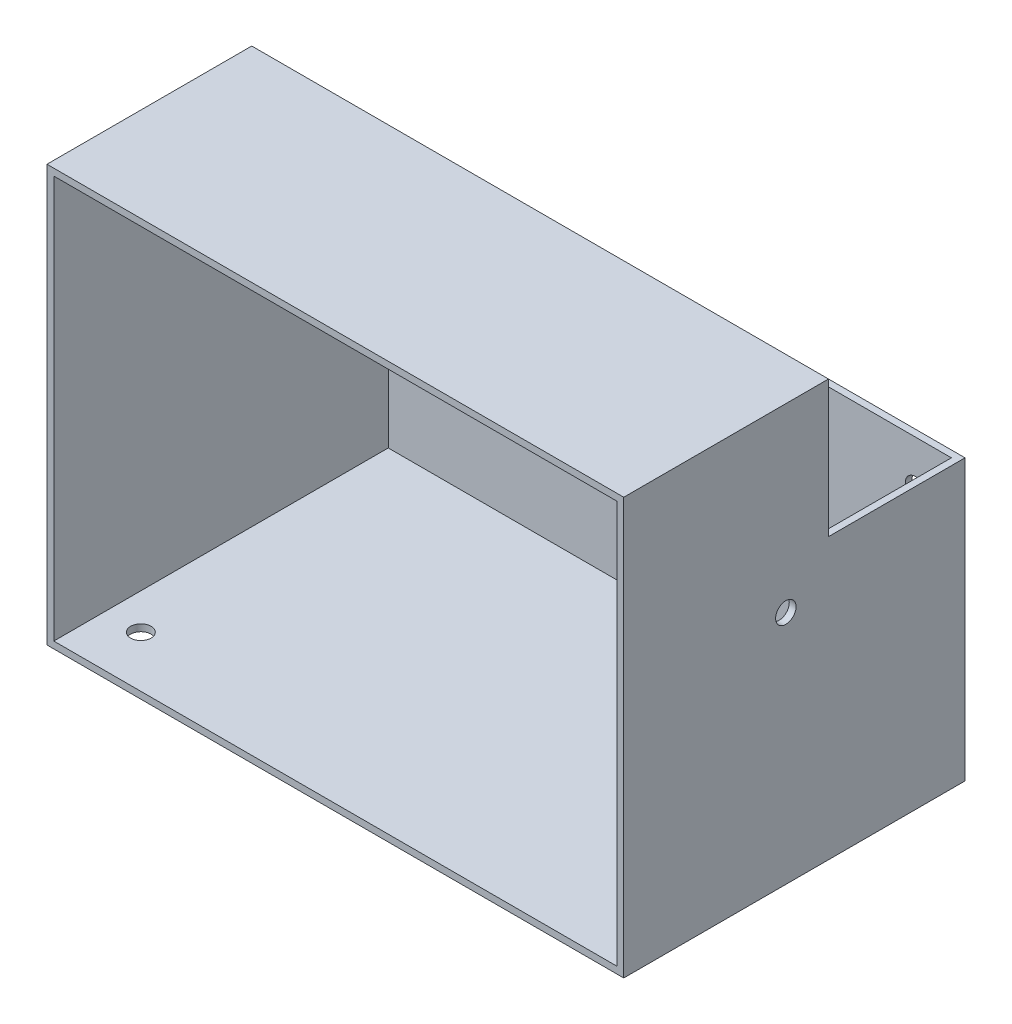
SolidWorks part; units mm, degrees
ref_plane "正面" through (0, 0, 0) normal (0, 0, 1) x (1, 0, 0)
ref_plane "平面" through (0, 0, 0) normal (0, 1, 0) x (1, 0, 0)
ref_plane "右側面" through (0, 0, 0) normal (1, 0, 0) x (0, 0, -1)
sketch "ｽｹｯﾁ2" plane through (0, 0, 0) normal (0, 1, 0) x (1, 0, 0)
  line L1 (-84.5, 50) -> (84.5, 50)
  line L2 (-84.5, 50) -> (-84.5, -50)
  line L3 (-84.5, -50) -> (84.5, -50)
  line L4 (84.5, 50) -> (84.5, -50)
  line L5 (-84.5, 50) -> (84.5, -50) construction
  line L6 (-84.5, -50) -> (84.5, 50) construction
  point P0 (0, 0)
  dimension "D1" = 169
  dimension "D2" = 100
extrude "ﾎﾞｽ - 押し出し2" add sketch "ｽｹｯﾁ2" along normal blind 122
sketch "ｽｹｯﾁ6" plane through (0, 0, 50) normal (0, 0, 1) x (1, 0, 0)
  line L0 (-84.5, 61) -> (84.5, 61) construction
  line L1 (-84.5, 122) -> (-84.5, 0) construction
  line L2 (84.5, 122) -> (84.5, 0) construction
  line L3 (0, 122) -> (0, 0) construction
  line L4 (-84.5, 122) -> (84.5, 122) construction
  line L5 (-84.5, 0) -> (84.5, 0) construction
  line L7 (-82.5, 120) -> (82.5, 120)
  line L8 (-82.5, 120) -> (-82.5, 2)
  line L9 (-82.5, 2) -> (82.5, 2)
  line L10 (82.5, 120) -> (82.5, 2)
  line L11 (-82.5, 120) -> (82.5, 2) construction
  line L12 (-82.5, 2) -> (82.5, 120) construction
  point P12 (0, 61)
  dimension "D1" = 2
  dimension "D2" = 2
extrude "ｶｯﾄ - 押し出し3" cut sketch "ｽｹｯﾁ6" against normal blind 98
sketch "ｽｹｯﾁ7" plane through (84.5, 0, 0) normal (1, 0, 0) x (0, 0, -1)
  line L1 (50, 122) -> (10, 122)
  line L2 (50, 122) -> (50, 82)
  line L3 (50, 82) -> (10, 82)
  line L4 (10, 122) -> (10, 82)
  dimension "D1" = 40
  dimension "D2" = 40
extrude "ｶｯﾄ - 押し出し4" cut sketch "ｽｹｯﾁ7" against normal through all
sketch "ｽｹｯﾁ8" plane through (0, 2, 0) normal (0, 1, 0) x (1, 0, 0)
  line L0 (0, 50) -> (0, -50) construction
  line L2 (-82.5, -50) -> (82.5, -50) construction
  line L3 (-82.5, -35) -> (82.5, -35) construction
  line L4 (-82.5, 48) -> (-82.5, -50) construction
  line L5 (82.5, 48) -> (82.5, -50) construction
  line L7 (-82.5, 50) -> (82.5, 50) construction
  circle A0 centre (-72, -35) radius 3
  circle A1 centre (72, -35) radius 3
  point P18 (0, 50)
  dimension "D2" = 6
  dimension "D1" = 15
  dimension "D3" = 10.5
extrude "ｶｯﾄ - 押し出し5" cut sketch "ｽｹｯﾁ8" against normal blind 10
sketch "ｽｹｯﾁ9" plane through (0, 0, -48) normal (0, 0, 1) x (1, 0, 0)
  line L1 (-82.5, 82) -> (82.5, 82) construction
  line L3 (-82.5, 67) -> (82.5, 67)
  line L4 (-82.5, 82) -> (-82.5, 2) construction
  line L5 (82.5, 2) -> (82.5, 82) construction
  circle A0 centre (-72, 67) radius 3
  circle A1 centre (72, 69) radius 3
  dimension "D2" = 6
  dimension "D1" = 15
  dimension "D3" = 10.5
  dimension "D4" = 10.5
extrude "ｶｯﾄ - 押し出し6" cut sketch "ｽｹｯﾁ9" against normal blind 10 contours A0 | A1
sketch "ｽｹｯﾁ10" plane through (84.5, 0, 0) normal (1, 0, 0) x (0, 0, -1)
  line L0 (-2.5, 0) -> (-2.5, 124) construction
  line L1 (-37.5, 122) -> (-37.5, 0) construction
  line L2 (-50, 122) -> (10, 122) construction
  line L3 (-50, 67) -> (50, 67) construction
  line L4 (-50, 122) -> (-50, 0) construction
  line L5 (10, 122) -> (10, 82) construction
  line L6 (50, 82) -> (50, 0) construction
  line L7 (-50, 0) -> (50, 0) construction
  line L8 (-50, 61) -> (50, 61) construction
  circle A0 centre (-2.5, 69) radius 3
  dimension "D2" = 6
  dimension "D1" = 55
  dimension "D3" = 12.5
  dimension "D4" = 12.5
extrude "ｶｯﾄ - 押し出し7" cut sketch "ｽｹｯﾁ10" against normal blind 10
